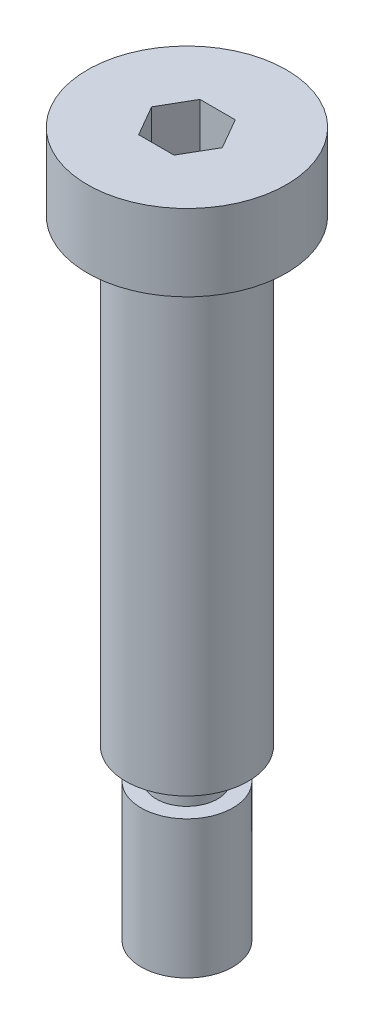
SolidWorks part; units mm, degrees
material "合金钢"
ref_plane "前视基准面" through (0, 0, 0) normal (0, 0, 1) x (1, 0, 0)
ref_plane "上视基准面" through (0, 0, 0) normal (0, 1, 0) x (1, 0, 0)
ref_plane "右视基准面" through (0, 0, 0) normal (1, 0, 0) x (0, 0, -1)
other "Configuration Table"
sketch "草图1" plane through (0, 0, 0) normal (0, 0, 1) x (1, 0, 0)
  line L0 (0, 0) -> (0, 14502.1657) construction
  line L1 (0, 46) -> (6.5, 46)
  line L2 (6.5, 46) -> (6.5, 41)
  line L3 (6.5, 41) -> (4, 41)
  line L4 (4, 41) -> (4, 11)
  line L5 (4, 11) -> (2, 11)
  line L6 (2, 11) -> (2, 9)
  line L7 (2, 9) -> (3, 9)
  line L8 (3, 9) -> (3, 0)
  line L9 (3, 0) -> (0, 0)
  line L10 (0, 0) -> (0, 46)
  dimension "D1" = 13
  dimension "D2" = 8
  dimension "D3" = 4
  dimension "D4" = 6
  dimension "D5" = 5
  dimension "D6" = 30
  dimension "D7" = 2
  dimension "D8" = 9
revolve "旋转1" add sketch "草图1" angle 360 about L0
sketch "草图2" plane through (0, 46, 0) normal (0, 1, 0) x (1, 0, 0)
  line L1 (1.1547, 2) -> (-1.1547, 2)
  line L2 (-1.1547, 2) -> (-2.3094, 0)
  line L3 (-2.3094, 0) -> (-1.1547, -2)
  line L4 (-1.1547, -2) -> (1.1547, -2)
  line L5 (1.1547, -2) -> (2.3094, 0)
  line L6 (2.3094, 0) -> (1.1547, 2)
  circle A0 centre (0, 0) radius 2 construction
  dimension "D1" = 4
extrude "切除-拉伸1" cut sketch "草图2" against normal blind 3
